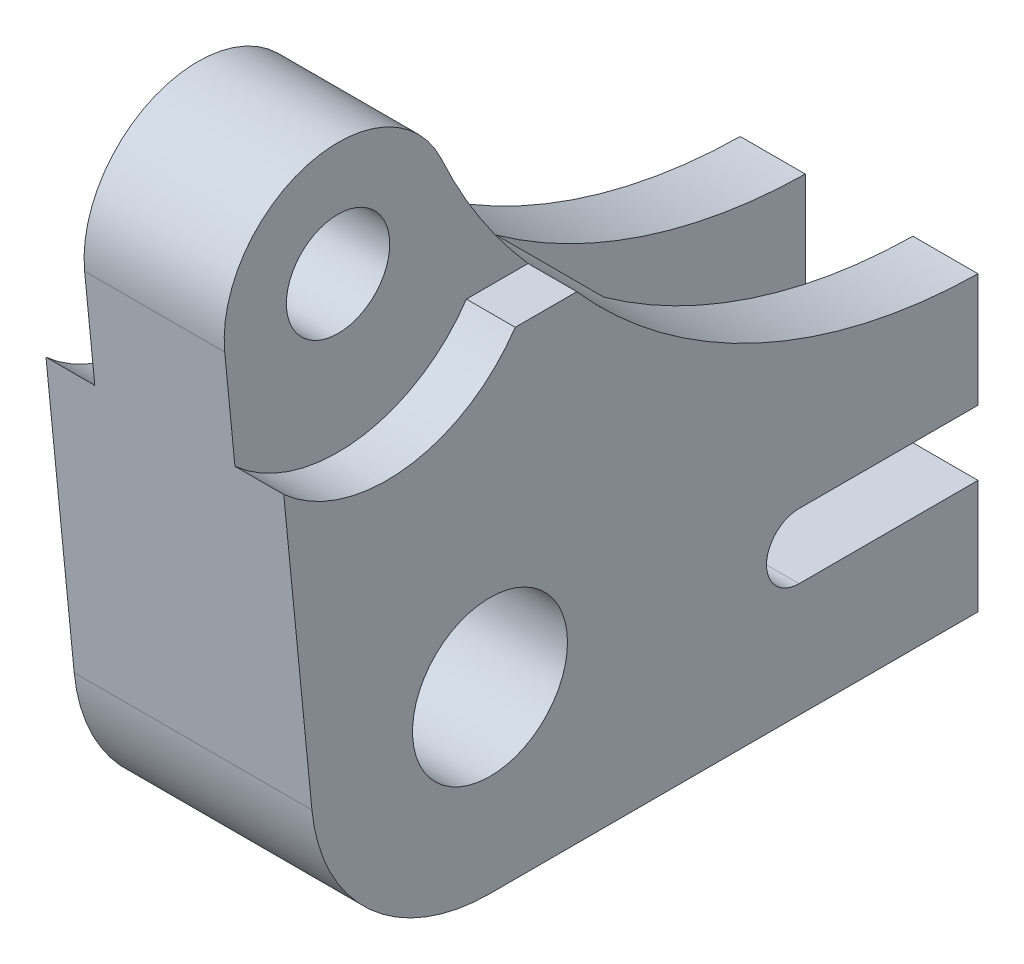
SolidWorks part; units mm, degrees
ref_plane "Front Plane" through (0, 0, 0) normal (0, 0, 1) x (1, 0, 0)
ref_plane "Top Plane" through (0, 0, 0) normal (0, 1, 0) x (1, 0, 0)
ref_plane "Right Plane" through (0, 0, 0) normal (1, 0, 0) x (0, 0, -1)
sketch "Sketch1" plane through (0, 0, 0) normal (1, 0, 0) x (0, 0, -1)
  line L0 (0, -22) -> (60, -22)
  line L1 (60, -22) -> (60, 14)
  line L5 (0, 0) -> (-12.6821, 47.3304) construction
  line L7 (-26.6152, 45.9633) -> (-21.8949, -2.1482)
  line L8 (0, 0) -> (0, 89.6467) construction
  arc A0 (-21.8949, -2.1482) -> (0, -22) centre (0, 0) ccw
  arc A1 (0, 53.2602) -> (-26.6152, 45.9633) centre (-12.6821, 47.3304) ccw
  arc A2 (60, 14) -> (0, 53.2602) centre (60.9911, 80.9927) cw
  circle A5 centre (-12.6821, 47.3304) radius 6.35
  circle A6 centre (0, 0) radius 9.525
  point P4 (-0.0007, 53.2618)
  point P9 (-118.704, 51.9705)
  point P12 (-0.0636, 53.2647)
  dimension "D1" = 44
  dimension "D2" = 67
  dimension "D3" = 15
  dimension "D5" = 28
  dimension "D6" = 36
  dimension "D8" = 12.7
  dimension "D9" = 19.05
  dimension "D4" = 49
  dimension "D7" = 60
extrude "Boss-Extrude1" add sketch "Sketch1" along normal mid plane 29.23
sketch "Sketch2" plane through (14.615, 0, 0) normal (1, 0, 0) x (0, 0, -1)
  line L0 (38, -4) -> (60, -4) construction
  line L1 (60, -22) -> (60, 14) construction
  line L2 (38, 0) -> (60, 0)
  line L3 (38, -8) -> (60, -8)
  arc A0 (38, 0) -> (38, -8) centre (38, -4) ccw
  arc A1 (60, -8) -> (60, 0) centre (60, -4) ccw
  point P4 (49, -4)
  dimension "D2" = 4
  dimension "D1" = 22
extrude "Cut-Extrude1" cut sketch "Sketch2" against normal through all
sketch "Sketch4" plane through (0, -22, 0) normal (0, -1, 0) x (1, 0, 0)
  line L0 (14.615, -60) -> (-14.615, -60) construction
  line L1 (-6.615, -60) -> (6.615, -60)
  line L2 (-6.615, -60) -> (-6.615, -22)
  line L3 (-6.615, -22) -> (6.615, -22)
  line L4 (6.615, -60) -> (6.615, -22)
  line L5 (0, 0) -> (0, -32.6421) construction
  dimension "D1" = 13.23
  dimension "D2" = 38
extrude "Cut-Extrude2" cut sketch "Sketch4" against normal through all
sketch "Sketch5" plane through (14.615, 0, 0) normal (1, 0, 0) x (0, 0, -1)
  line L0 (3.0996, 36.7504) -> (10.6759, 36.7504)
  line L1 (-26.6152, 45.9633) -> (-21.8949, -2.1482) construction
  line L2 (-26.6152, 45.9633) -> (-25.361, 33.1795)
  arc A0 (-25.361, 33.1795) -> (3.0996, 36.7504) centre (-12.6821, 47.3304) ccw
  arc A1 (0, 53.2602) -> (60, 14) centre (60.9911, 80.9927) ccw construction
  arc A2 (0, 53.2602) -> (10.6759, 36.7504) centre (60.9911, 80.9927) ccw
  arc A3 (0, 53.2602) -> (-26.6152, 45.9633) centre (-12.6821, 47.3304) ccw construction
  arc A4 (0, 53.2602) -> (-26.6152, 45.9633) centre (-12.6821, 47.3304) ccw
  dimension "D1" = 38
  dimension "D2" = 10.58
extrude "Cut-Extrude3" cut sketch "Sketch5" against normal blind 6
mirror "Mirror1" about plane through (0, 0, 0) normal (1, 0, 0) of "Cut-Extrude3"
